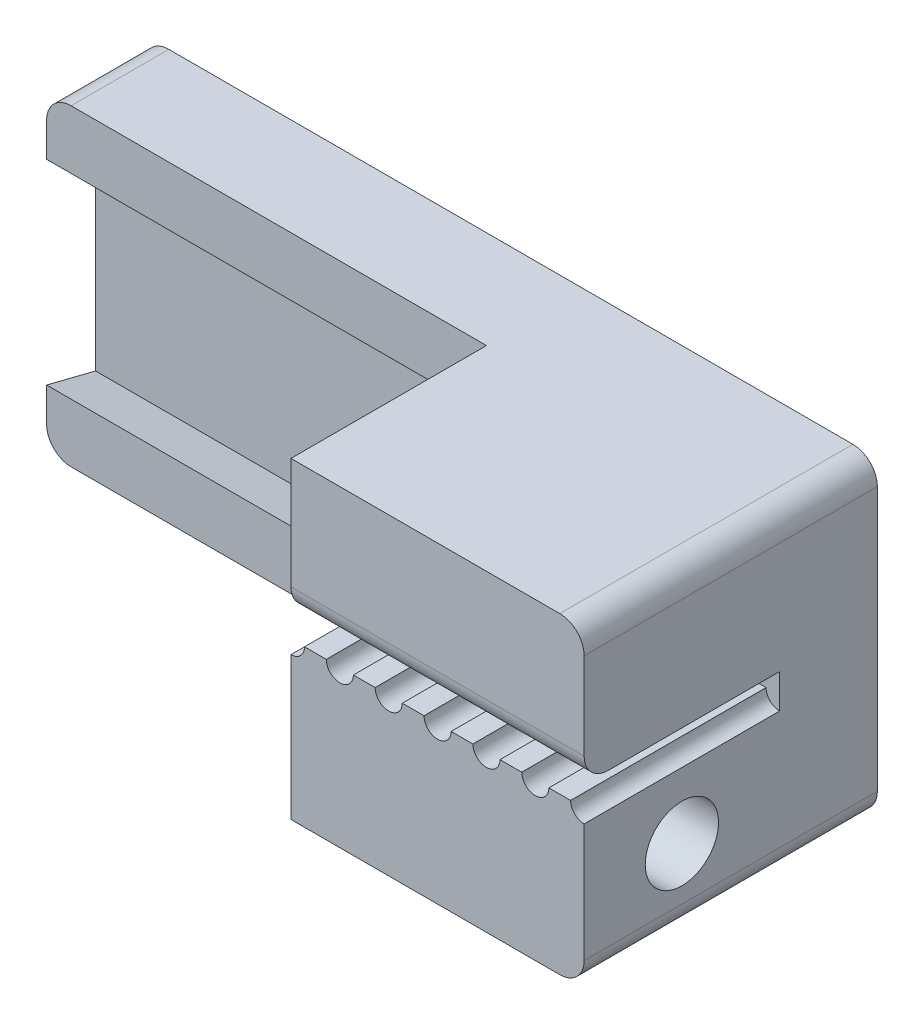
SolidWorks part; units mm, degrees
material "PC High Viscosity"
ref_plane "Front Plane" through (0, 0, 0) normal (0, 0, 1) x (1, 0, 0)
ref_plane "Top Plane" through (0, 0, 0) normal (0, 1, 0) x (1, 0, 0)
ref_plane "Right Plane" through (0, 0, 0) normal (1, 0, 0) x (0, 0, -1)
sketch "Sketch4" plane through (0, 0, 0) normal (0, 0, 1) x (1, 0, 0)
  line L4 (12, 1.1) -> (12, 11.9)
  line L7 (11, 12.9) -> (-17, 12.9)
  line L8 (11, 0.1) -> (-17, 0.1)
  line L9 (-18, 11.9) -> (-18, 1.1)
  arc A0 (11, 12.9) -> (12, 11.9) centre (11, 11.9) cw
  arc A1 (11, 0.1) -> (12, 1.1) centre (11, 1.1) ccw
  arc A5 (-17, 0.1) -> (-18, 1.1) centre (-17, 1.1) cw
  arc A6 (-17, 12.9) -> (-18, 11.9) centre (-17, 11.9) ccw
extrude "Boss-Extrude1" add sketch "Sketch4" along normal blind 12
sketch "Sketch5" plane through (0, 0, 12) normal (0, 0, 1) x (1, 0, 0)
  line L0 (11.445, 6.5) -> (10.555, 6.5)
  line L1 (9.445, 6.5) -> (8.555, 6.5)
  line L2 (7.445, 6.5) -> (6.555, 6.5)
  line L3 (5.445, 6.5) -> (4.555, 6.5)
  line L4 (0, 7.345) -> (12, 7.345)
  line L5 (12, 7.345) -> (12, 5.945)
  line L6 (0, 7.345) -> (0, 5.945)
  line L7 (3.445, 6.5) -> (2.555, 6.5)
  line L8 (1.445, 6.5) -> (0.555, 6.5)
  arc A0 (9.445, 6.5) -> (10.555, 6.5) centre (10, 6.5) ccw
  arc A1 (11.445, 6.5) -> (12, 5.945) centre (12, 6.5) ccw
  arc A2 (7.445, 6.5) -> (8.555, 6.5) centre (8, 6.5) ccw
  arc A3 (6.555, 6.5) -> (5.445, 6.5) centre (6, 6.5) cw
  arc A4 (4.555, 6.5) -> (3.445, 6.5) centre (4, 6.5) cw
  arc A5 (1.445, 6.5) -> (2.555, 6.5) centre (2, 6.5) ccw
  arc A6 (0.555, 6.5) -> (0, 5.945) centre (0, 6.5) cw
extrude "Cut-Extrude1" cut sketch "Sketch5" against normal blind 8
fillet "Fillet1" radius 1 1 edges at (6, 7.345, 12)
sketch "Sketch7" plane through (-18, 0, 0) normal (-1, 0, 0) x (0, 0, 1)
  line L0 (4, 10.5) -> (4, 12.9)
  line L1 (2, 11) -> (4, 10.5)
  line L3 (4, 2.5) -> (2, 2)
  line L4 (2, 2) -> (2, 11)
  line L7 (4, 12.9) -> (12, 12.9)
  line L8 (12, 12.9) -> (12, 0.1)
  line L9 (12, 0.1) -> (4, 0.1)
  line L11 (4, 0.1) -> (4, 2.5)
extrude "Cut-Extrude3" cut sketch "Sketch7" against normal up to surface (18 mm away) up to face at (0, 6.9436, 8.6414)
sketch "Sketch6" plane through (12, 0, 0) normal (-1, 0, 0) x (0, 0, 1)
  circle A0 centre (8, 3.25) radius 1.5
  point P0 (0, 0)
extrude "Cut-Extrude2" cut sketch "Sketch6" along normal up to surface (12 mm away) up to face at (0, 6.6706, 6.7082)
